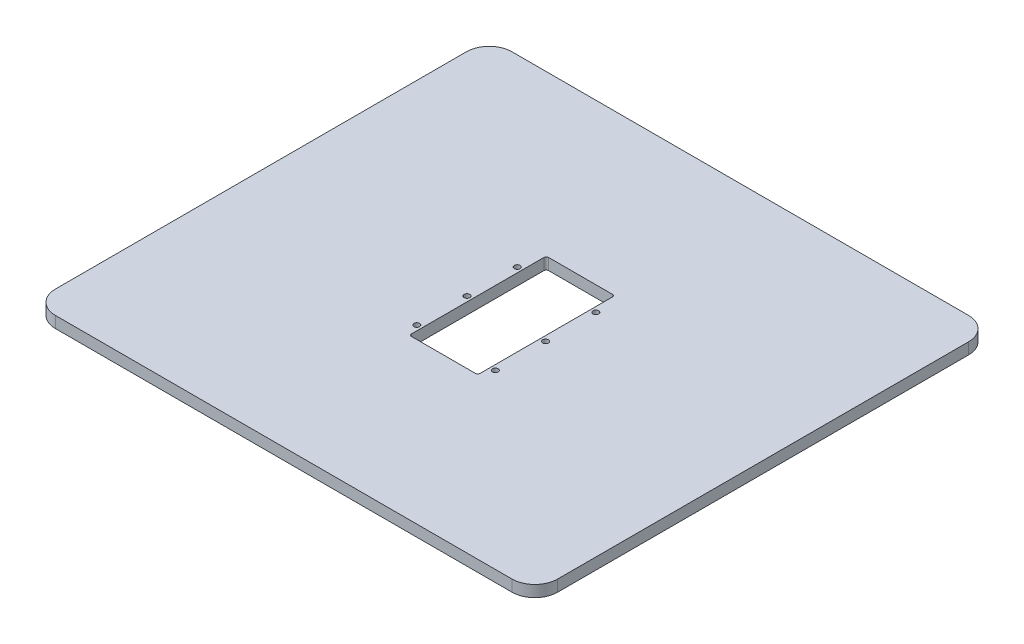
SolidWorks part; units mm, degrees
ref_plane "Plano frontal" through (0, 0, 0) normal (0, 0, 1) x (1, 0, 0)
ref_plane "Plano superior" through (0, 0, 0) normal (0, 1, 0) x (1, 0, 0)
ref_plane "Plano direito" through (0, 0, 0) normal (1, 0, 0) x (0, 0, -1)
sketch "Esboço1" plane through (0, 0, 0) normal (0, 1, 0) x (1, 0, 0)
  line L1 (100, -100) -> (-100, -100)
  line L2 (110, -90) -> (110, 90)
  line L3 (100, 100) -> (-100, 100)
  line L4 (-110, -90) -> (-110, 90)
  line L5 (110, -100) -> (-110, 100) construction
  line L6 (110, 100) -> (-110, -100) construction
  line L10 (-110, 0) -> (110, 0) construction
  line L11 (0, 30) -> (0, -30) construction
  line L12 (14, 30) -> (-14, 30)
  line L13 (15, 29) -> (15, -29)
  line L14 (14, -30) -> (-14, -30)
  line L15 (-15, 29) -> (-15, -29)
  line L16 (15, 30) -> (-15, -30) construction
  line L17 (15, -30) -> (-15, 30) construction
  arc A0 (100, -100) -> (110, -90) centre (100, -90) ccw
  arc A1 (-100, -100) -> (-110, -90) centre (-100, -90) cw
  arc A2 (-100, 100) -> (-110, 90) centre (-100, 90) ccw
  arc A3 (110, 90) -> (100, 100) centre (100, 90) ccw
  circle A8 centre (17.2, 19.5) radius 1.25
  circle A9 centre (17.2, -2.5) radius 1.25
  circle A10 centre (17.2, -24.5) radius 1.25
  arc A11 (15, -29) -> (14, -30) centre (14, -29) cw
  arc A12 (-14, -30) -> (-15, -29) centre (-14, -29) cw
  arc A13 (14, 30) -> (15, 29) centre (14, 29) cw
  arc A14 (-14, 30) -> (-15, 29) centre (-14, 29) ccw
  circle A15 centre (-17.2, -24.5) radius 1.25
  circle A16 centre (-17.2, -2.5) radius 1.25
  circle A17 centre (-17.2, 19.5) radius 1.25
  point P0 (0, 0)
  point P18 (-100, 0)
  point P19 (100, 0)
  point P32 (0, 0)
  dimension "D3" = 10
  dimension "D8" = 60
  dimension "D10" = 2.5
  dimension "D13" = 2.5
  dimension "D16" = 2.5
  dimension "D17" = 1
  dimension "D1" = 200
  dimension "D2" = 220
  dimension "D9" = 30
  dimension "D11" = 10.5
  dimension "D12" = 22
  dimension "D14" = 2.2
  dimension "D15" = 22
extrude "Ressalto-extrusão1" add sketch "Esboço1" along normal blind 5
